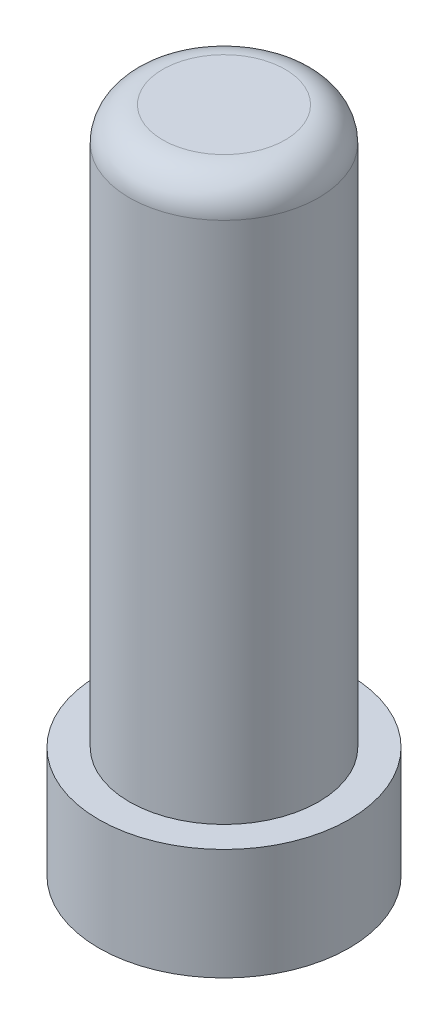
SolidWorks part; units mm, degrees
ref_plane "前视基准面" through (0, 0, 0) normal (0, 0, 1) x (1, 0, 0)
ref_plane "上视基准面" through (0, 0, 0) normal (0, 1, 0) x (1, 0, 0)
ref_plane "右视基准面" through (0, 0, 0) normal (1, 0, 0) x (0, 0, -1)
other "Configuration Table"
sketch "草图1" plane through (0, 0, 0) normal (0, 1, 0) x (1, 0, 0)
  circle A0 centre (0, 0) radius 2.25
  dimension "D1" = 4.5
extrude "凸台-拉伸1" add sketch "草图1" along normal blind 2
sketch "草图2" plane through (0, 2, 0) normal (0, 1, 0) x (1, 0, 0)
  circle A0 centre (0, 0) radius 1.7
  dimension "D1" = 3.4
extrude "凸台-拉伸2" add sketch "草图2" along normal blind 10
fillet "圆角1" radius 0.6 1 edges at (0, 12, 1.7)
